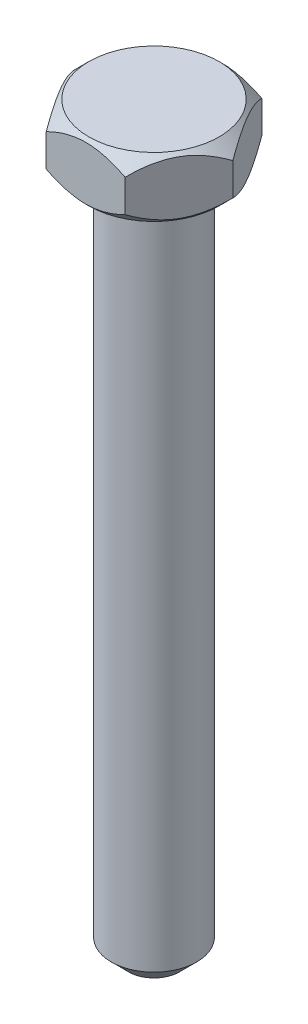
SolidWorks part; units mm, degrees
ref_plane "Спереди" through (0, 0, 0) normal (0, 0, 1) x (1, 0, 0)
ref_plane "Сверху" through (0, 0, 0) normal (0, 1, 0) x (1, 0, 0)
ref_plane "Справа" through (0, 0, 0) normal (1, 0, 0) x (0, 0, -1)
sketch "Эскиз1" plane through (0, 0, 0) normal (0, 1, 0) x (1, 0, 0)
  line L0 (-2.3094, 4) -> (2.3094, 4)
  line L1 (2.3094, 4) -> (4.6188, 0)
  line L2 (4.6188, 0) -> (2.3094, -4)
  line L3 (2.3094, -4) -> (-2.3094, -4)
  line L4 (-2.3094, -4) -> (-4.6188, 0)
  line L5 (-4.6188, 0) -> (-2.3094, 4)
  dimension "D5" = 4
  dimension "D2" = 120
  dimension "D3" = 120
  dimension "D4" = 120
  dimension "D6" = 4
  dimension "D7" = 4
  dimension "D8" = 4
  dimension "D9" = 4
  dimension "D10" = 120
  dimension "D11" = 4
extrude "Вытянуть1" add sketch "Эскиз1" against normal blind 3.5
sketch "Эскиз5" plane through (0, -3.5, 0) normal (0, -1, 0) x (1, 0, 0)
  circle A0 centre (0, 0) radius 2.5
  dimension "D1" = 5
extrude "Вытянуть2" add sketch "Эскиз5" along normal blind 40
chamfer "Фаска1" distance 1 angle 45 1 edges at (0, -43.5, -2.5)
ref_axis "Ось1" through (0, -3.5, 0) along (0, -1, 0)
ref_plane "Плоскость1" through (0, 0, 0) normal (0, 0, 1) x (1, 0, 0)
sketch "Эскиз4" plane through (0, 0, 0) normal (0, 0, 1) x (1, 0, 0)
  line L0 (-4.6188, -0.8) -> (-3.8188, 0)
  line L1 (-4.6188, -3.5) -> (-4.6188, 0) construction
  line L2 (-4.6188, 0) -> (-2.3094, 0) construction
  line L3 (-3.8188, 0) -> (-4.6188, 0)
  line L4 (-4.6188, 0) -> (-4.6188, -0.8)
  line L5 (-4.6188, -2.7) -> (-3.8188, -3.5)
  line L6 (-4.6188, -3.5) -> (-2.3094, -3.5) construction
  line L7 (-3.8188, -3.5) -> (-4.6188, -3.5)
  line L8 (-4.6188, -3.5) -> (-4.6188, -2.7)
  dimension "D1" = 0.8
  dimension "D2" = 0.8
  dimension "D3" = 0.8
  dimension "D4" = 0.8
revolve "Вырез-Повернуть1" cut sketch "Эскиз4" angle 360 about axis through (0, -3.5, 0) along (0, -1, 0)
